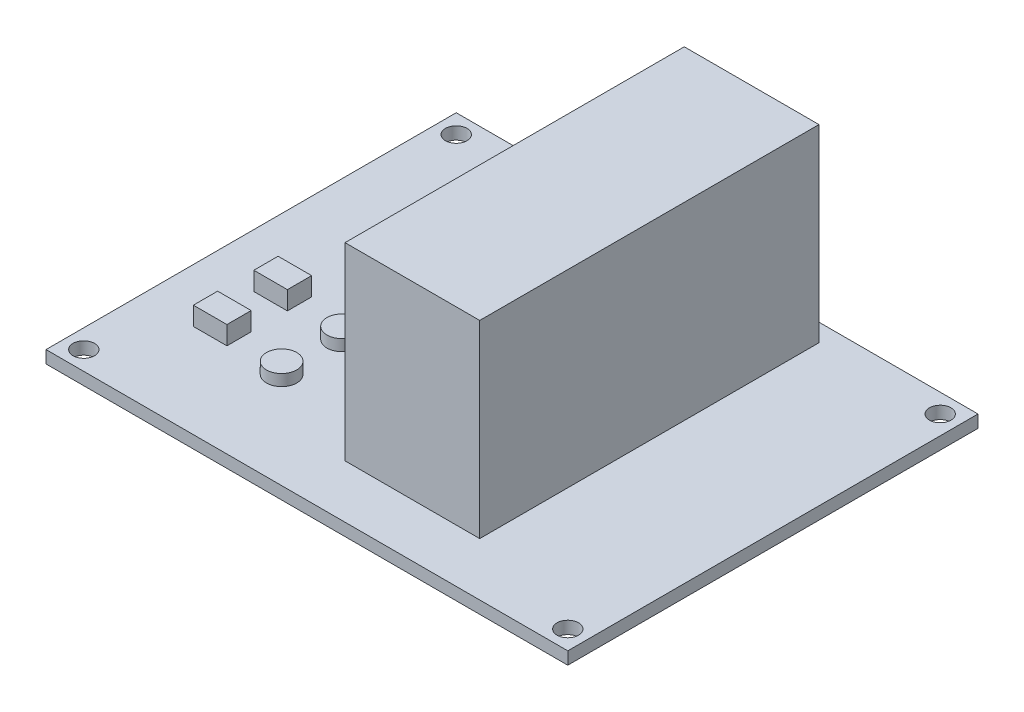
SolidWorks part; units mm, degrees
ref_plane "Front Plane" through (0, 0, 0) normal (0, 0, 1) x (1, 0, 0)
ref_plane "Top Plane" through (0, 0, 0) normal (0, 1, 0) x (1, 0, 0)
ref_plane "Right Plane" through (0, 0, 0) normal (1, 0, 0) x (0, 0, -1)
sketch "Sketch1" plane through (0, 0, 0) normal (0, 1, 0) x (1, 0, 0)
  line L1 (-34.515, -27.135) -> (34.515, -27.135)
  line L2 (-34.515, -27.135) -> (-34.515, 27.135)
  line L3 (-34.515, 27.135) -> (34.515, 27.135)
  line L4 (34.515, -27.135) -> (34.515, 27.135)
  line L5 (-34.515, -27.135) -> (34.515, 27.135) construction
  line L6 (-34.515, 27.135) -> (34.515, -27.135) construction
  point P0 (0, 0)
  dimension "D1" = 69.03
  dimension "D2" = 54.27
extrude "Boss-Extrude1" add sketch "Sketch1" along normal blind 1.65
sketch "Sketch2" plane through (0, 1.65, 0) normal (0, 1, 0) x (1, 0, 0)
  line L0 (-34.515, 27.135) -> (-34.515, -27.135) construction
  line L2 (-34.515, -27.135) -> (34.515, -27.135) construction
  line L5 (34.515, 27.135) -> (-34.515, 27.135) construction
  circle A0 centre (-16.095, -14.385) radius 2
  circle A1 centre (-16.095, -6.385) radius 2
  dimension "D1" = 18.42
  dimension "D3" = 8
  dimension "D2" = 12.75
extrude "Boss-Extrude2" add sketch "Sketch2" along normal blind 1.5
sketch "Sketch3" plane through (0, 1.65, 0) normal (0, 1, 0) x (1, 0, 0)
  line L0 (-34.515, -27.135) -> (34.515, -27.135) construction
  line L1 (-27.415, -11.53) -> (-22.975, -11.53)
  line L2 (-27.415, -11.53) -> (-27.415, -14.74)
  line L3 (-27.415, -14.74) -> (-22.975, -14.74)
  line L4 (-22.975, -11.53) -> (-22.975, -14.74)
  line L5 (-27.415, -11.53) -> (-22.975, -14.74) construction
  line L6 (-27.415, -14.74) -> (-22.975, -11.53) construction
  line L7 (-34.515, 27.135) -> (-34.515, -27.135) construction
  line L9 (-27.415, -3.53) -> (-22.975, -3.53)
  line L10 (-27.415, -3.53) -> (-27.415, -6.74)
  line L11 (-27.415, -6.74) -> (-22.975, -6.74)
  line L12 (-22.975, -3.53) -> (-22.975, -6.74)
  line L13 (-27.415, -3.53) -> (-22.975, -6.74) construction
  line L14 (-27.415, -6.74) -> (-22.975, -3.53) construction
  point P0 (-25.195, -13.135)
  point P10 (-25.195, -5.135)
  dimension "D1" = 14
  dimension "D2" = 9.32
  dimension "D3" = 4.44
  dimension "D4" = 3.21
  dimension "D5" = 3.21
  dimension "D6" = 4.44
  dimension "D7" = 8
extrude "Boss-Extrude3" add sketch "Sketch3" along normal blind 2.44
sketch "Sketch4" plane through (0, 1.65, 0) normal (0, 1, 0) x (1, 0, 0)
  line L0 (34.515, -27.135) -> (34.515, 27.135) construction
  line L1 (-1.985, 24.775) -> (15.835, 24.775)
  line L2 (-1.985, 24.775) -> (-1.985, -20.105)
  line L3 (-1.985, -20.105) -> (15.835, -20.105)
  line L4 (15.835, 24.775) -> (15.835, -20.105)
  line L5 (-34.515, -27.135) -> (34.515, -27.135) construction
  dimension "D1" = 17.82
  dimension "D2" = 44.88
  dimension "D3" = 18.68
  dimension "D4" = 7.03
extrude "Boss-Extrude4" add sketch "Sketch4" along normal blind 25
hole_wizard "#4 Clearance Hole1" positions "Sketch5" profile "Sketch6" hole size "#4" standard "ANSI Inch" end condition through all
sketch "Sketch5" plane through (18.6603, 1.65, 81.8304) normal (0, 1, 0) x (0, 0, 1)
  point P0 (-106.4654, -50.6753)
  point P1 (-57.1954, -50.6753)
  point P2 (-57.1954, 13.3547)
  point P3 (-106.4654, 13.3547)
sketch "Sketch6" plane through (-32.015, 1.65, -24.635) normal (1, 0, 0) x (0, 0, 1)
  line L0 (0, 0) -> (0, 1.65)
  line L1 (0, 1.65) -> (1.4224, 1.65)
  line L2 (1.4224, 1.65) -> (1.4224, 0)
  line L5 (1.4224, 0) -> (0, 0)
  line L11 (0, -6.35) -> (0, 107.95) construction
  dimension "Thru Hole Dia." = 2.8448
  dimension "Thru Hole Depth" = 1.65
